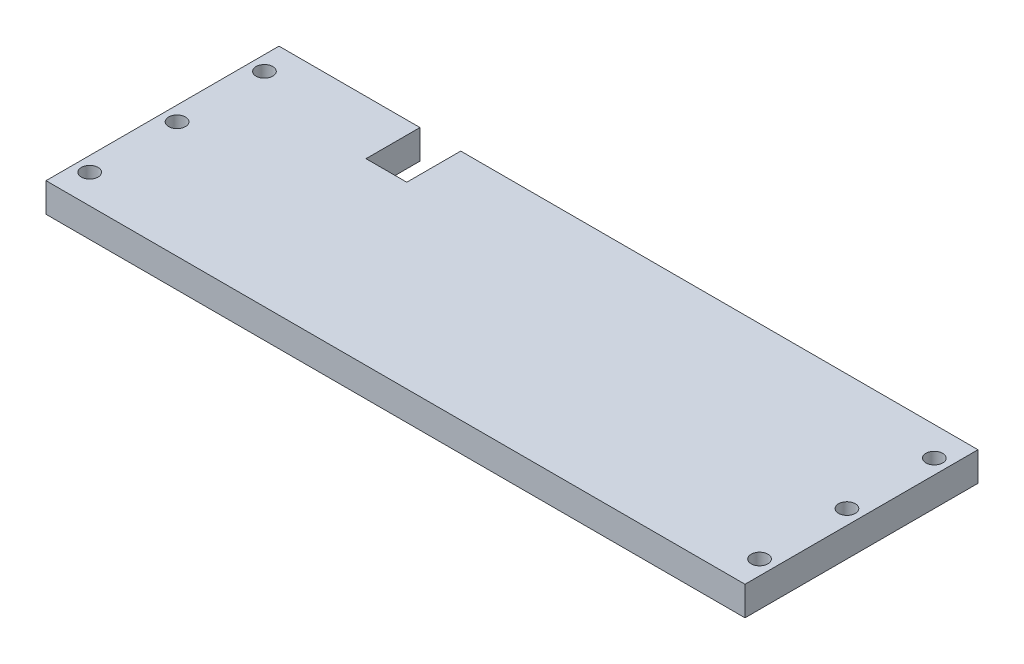
SolidWorks part; units mm, degrees
ref_plane "Front Plane" through (0, 0, 0) normal (0, 0, 1) x (1, 0, 0)
ref_plane "Top Plane" through (0, 0, 0) normal (0, 1, 0) x (1, 0, 0)
ref_plane "Right Plane" through (0, 0, 0) normal (1, 0, 0) x (0, 0, -1)
sketch "Sketch1" plane through (0, 0, 0) normal (0, 1, 0) x (1, 0, 0)
  line L1 (0, 0) -> (-152.4, 0)
  line L2 (0, 0) -> (0, 50.8)
  line L3 (0, 50.8) -> (-152.4, 50.8)
  line L4 (-152.4, 0) -> (-152.4, 50.8)
  dimension "D1" = 50.8
  dimension "D2" = 152.4
extrude "Boss-Extrude1" add sketch "Sketch1" along normal blind 6.35
sketch "Sketch2" plane through (0, 6.35, 0) normal (0, 1, 0) x (1, 0, 0)
  line L0 (0, 50.8) -> (-152.4, 50.8) construction
  line L1 (0, 0) -> (0, 50.8) construction
  line L2 (-152.4, 50.8) -> (-152.4, 0) construction
  circle A0 centre (-149.225, 44.45) radius 1.8288
  circle A1 centre (-149.225, 25.4) radius 1.8288
  circle A2 centre (-149.225, 6.35) radius 1.8288
  circle A3 centre (-3.175, 25.4) radius 1.8288
  circle A4 centre (-3.175, 44.45) radius 1.8288
  circle A5 centre (-3.175, 6.35) radius 1.8288
  dimension "D10" = 3.6576
  dimension "D11" = 3.6576
  dimension "D12" = 3.6576
  dimension "D13" = 3.6576
  dimension "D14" = 3.6576
  dimension "D15" = 3.6576
  dimension "D16" = 3.175
  dimension "D17" = 3.175
  dimension "D18" = 3.175
  dimension "D1" = 6.35
  dimension "D2" = 25.4
  dimension "D3" = 44.45
  dimension "D4" = 6.35
  dimension "D5" = 25.4
  dimension "D6" = 44.45
  dimension "D7" = 3.175
  dimension "D8" = 3.175
  dimension "D9" = 3.175
extrude "Cut-Extrude1" cut sketch "Sketch2" against normal blind 6.35
sketch "Sketch5" plane through (0, 6.35, 0) normal (0, 1, 0) x (1, 0, 0)
  line L0 (-121.666, 50.8) -> (-121.666, 39.035)
  line L1 (0, 50.8) -> (-152.4, 50.8) construction
  line L2 (-121.666, 39.035) -> (-112.776, 39.035)
  line L3 (-112.776, 39.035) -> (-112.776, 50.8)
  line L5 (-152.4, 50.8) -> (-152.4, 0) construction
  line L6 (-121.666, 50.8) -> (-112.776, 50.8)
  dimension "D1" = 39.624
  dimension "D2" = 8.89
extrude "Cut-Extrude2" cut sketch "Sketch5" against normal through all
